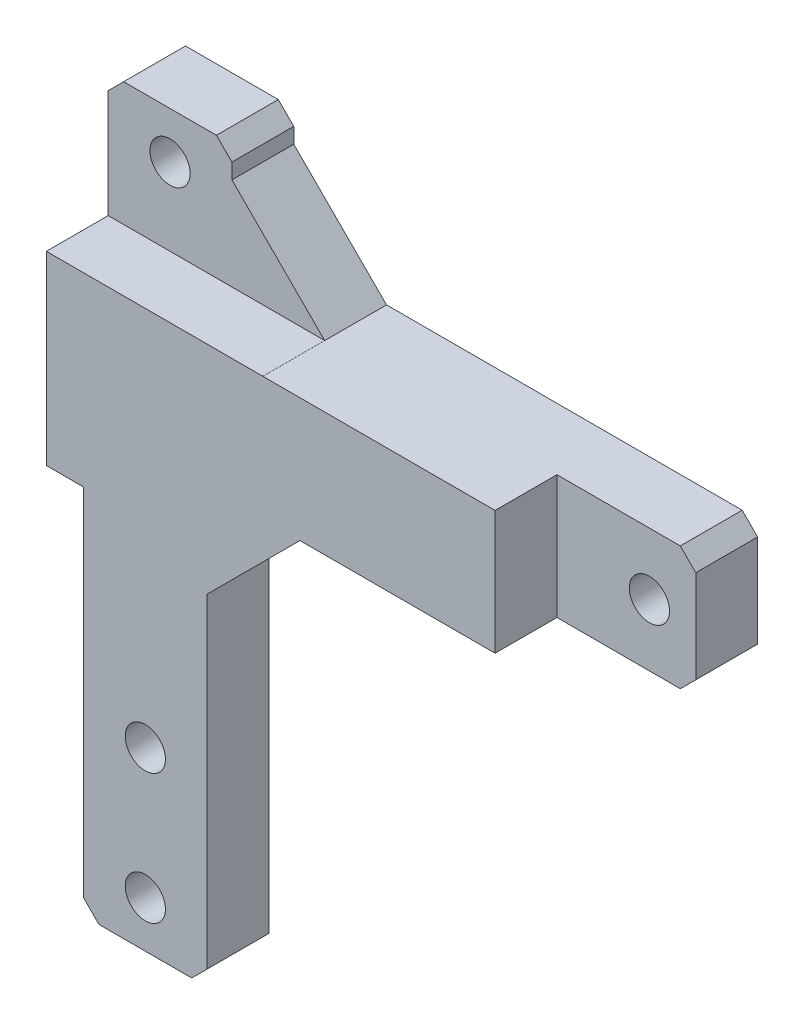
SolidWorks part; units mm, degrees
ref_plane "前视基准面" through (0, 0, 0) normal (0, 0, 1) x (1, 0, 0)
ref_plane "上视基准面" through (0, 0, 0) normal (0, 1, 0) x (1, 0, 0)
ref_plane "右视基准面" through (0, 0, 0) normal (1, 0, 0) x (0, 0, -1)
other "Configuration Table"
sketch "草图1" plane through (0, 0, 0) normal (0, 0, 1) x (1, 0, 0)
  line L0 (-4.3, -2.5) -> (9.5, -2.5)
  line L1 (-5.5, 1.5) -> (9.5, 1.5)
  line L4 (9.5, 1.5) -> (9.5, -2.5)
  line L8 (-9.5, 1.5) -> (-9.5, 5.5)
  line L9 (-9.5, 5.5) -> (-5.5, 5.5)
  line L11 (-5.5, 1.5) -> (-5.5, 5.5)
  line L12 (-9.5, 1.5) -> (-9.5, -4.5)
  line L13 (-8.3, -4.5) -> (-8.3, -16.5)
  line L14 (-8.3, -16.5) -> (-4.3, -16.5)
  line L15 (-4.3, -16.5) -> (-4.3, -2.5)
  line L16 (-9.5, -4.5) -> (-8.3, -4.5)
  circle A0 centre (8, -0.5) radius 0.65
  circle A1 centre (-7.5, 4) radius 0.65
  circle A2 centre (-6.3, -15) radius 0.65
  circle A3 centre (-6.3, -10.8) radius 0.65
  point P0 (0, 0)
  dimension "D3" = 1.3
  dimension "D8" = 1.3
  dimension "D15" = 1.3
  dimension "D16" = 1.3
  dimension "D2" = 6
  dimension "D4" = 2
  dimension "D5" = 1.5
  dimension "D6" = 10
  dimension "D7" = 4
  dimension "D9" = 2
  dimension "D10" = 1.5
  dimension "D11" = 4
  dimension "D12" = 4
  dimension "D13" = 2
  dimension "D14" = 19
  dimension "D17" = 4.2
  dimension "D18" = 1.5
  dimension "D19" = 2
extrude "凸台-拉伸1" add sketch "草图1" along normal blind 4
sketch "草图2" plane through (0, 0, 0) normal (0, 0, 1) x (1, 0, 0)
  line L0 (-8.3, -4.8687) -> (-4.3, -4.8687)
  line L10 (9.5, -2.5) -> (9.5, 1.5)
  line L11 (9.5, 1.5) -> (-5.5, 1.5)
  line L12 (-5.5, 1.5) -> (-5.5, 5.5)
  line L13 (-5.5, 5.5) -> (-9.5, 5.5)
  line L14 (-9.5, 5.5) -> (-9.5, -4.5)
  line L15 (-9.5, -4.5) -> (-8.3, -4.5)
  line L16 (-8.3, -4.5) -> (-8.3, -16.5)
  line L17 (-8.3, -16.5) -> (-4.3, -16.5)
  line L18 (-4.3, -16.5) -> (-4.3, -2.5)
  line L19 (-4.3, -2.5) -> (9.5, -2.5)
  line L26 (-8.3, -4.8687) -> (-8.3, -16.5)
  line L27 (-8.3, -16.5) -> (-4.3, -16.5)
  line L28 (-4.3, -16.5) -> (-4.3, -4.8687)
  circle A0 centre (-6.3, -15) radius 0.65 construction
  circle A1 centre (-6.3, -10.8) radius 0.65 construction
  circle A2 centre (-6.3, -15) radius 0.65
  circle A3 centre (-6.3, -10.8) radius 0.65
  dimension "D1" = 0
extrude "切除-拉伸1" cut sketch "草图2" along normal blind 2
sketch "草图3" plane through (0, 0, 4) normal (0, 0, -1) x (-1, 0, 0)
  line L0 (-5.0101, 1.5) -> (-5.0101, -2.5)
  line L1 (5.5, 1.5011) -> (9.5, 1.5011)
  line L10 (-9.5, 1.5) -> (-9.5, -2.5)
  line L11 (-9.5, -2.5) -> (4.3, -2.5)
  line L12 (4.3, -2.5) -> (4.3, -4.8687)
  line L13 (4.3, -4.8687) -> (8.3, -4.8687)
  line L14 (8.3, -4.8687) -> (8.3, -4.5)
  line L15 (8.3, -4.5) -> (9.5, -4.5)
  line L16 (9.5, -4.5) -> (9.5, 5.5)
  line L17 (9.5, 5.5) -> (5.5, 5.5)
  line L18 (5.5, 5.5) -> (5.5, 1.5)
  line L19 (5.5, 1.5) -> (-9.5, 1.5)
  line L20 (-9.5, 1.5) -> (-9.5, -2.5)
  line L21 (-9.5, -2.5) -> (-5.0101, -2.5)
  line L26 (9.5, 1.5011) -> (9.5, 5.5)
  line L27 (9.5, 5.5) -> (5.5, 5.5)
  line L28 (5.5, 5.5) -> (5.5, 1.5011)
  line L29 (-5.0101, 1.5) -> (-9.5, 1.5)
  circle A0 centre (-8, -0.5) radius 0.65 construction
  circle A1 centre (7.5, 4) radius 0.65 construction
  circle A2 centre (-8, -0.5) radius 0.65
  circle A3 centre (7.5, 4) radius 0.65
  dimension "D1" = 0
extrude "切除-拉伸2" cut sketch "草图3" along normal blind 2
chamfer "倒角1" distance 3 angle 45 2 edges at (-4.3, -2.5, 2) (-5.5, 1.5, 2)
chamfer "倒角2" distance 0.5 angle 45 6 edges at (-4.3, -16.5, 3) (-8.3, -16.5, 3) (-9.5, 5.5, 1) (9.5, -2.5, 1) (9.5, 1.5, 1) (-5.5, 5.5, 1)
